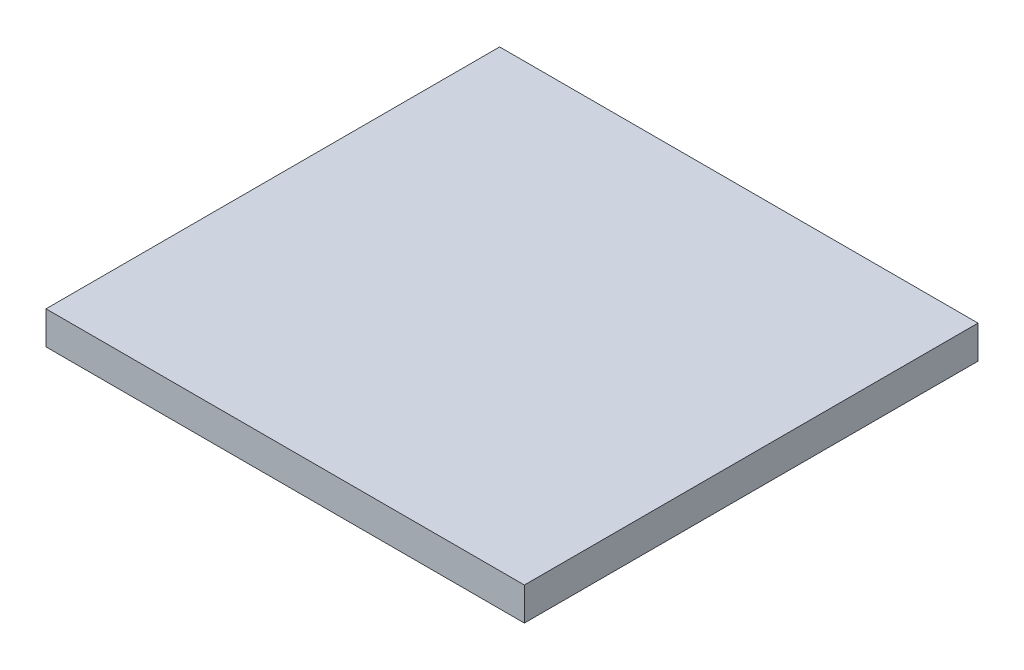
SolidWorks part; units mm, degrees
ref_plane "Front Plane" through (0, 0, 0) normal (0, 0, 1) x (1, 0, 0)
ref_plane "Top Plane" through (0, 0, 0) normal (0, 1, 0) x (1, 0, 0)
ref_plane "Right Plane" through (0, 0, 0) normal (1, 0, 0) x (0, 0, -1)
other "Configuration Table"
sketch "Sketch1" plane through (0, 0, 0) normal (0, 0, 1) x (1, 0, 0)
  line L1 (60, 822) -> (640, 822)
  line L2 (60, 822) -> (60, 862)
  line L3 (60, 862) -> (640, 862)
  line L4 (640, 822) -> (640, 862)
extrude "OVEN_sicak_dolap_pu_alt_1" add sketch "Sketch1" against normal blind 550 from offset 30 separate body
